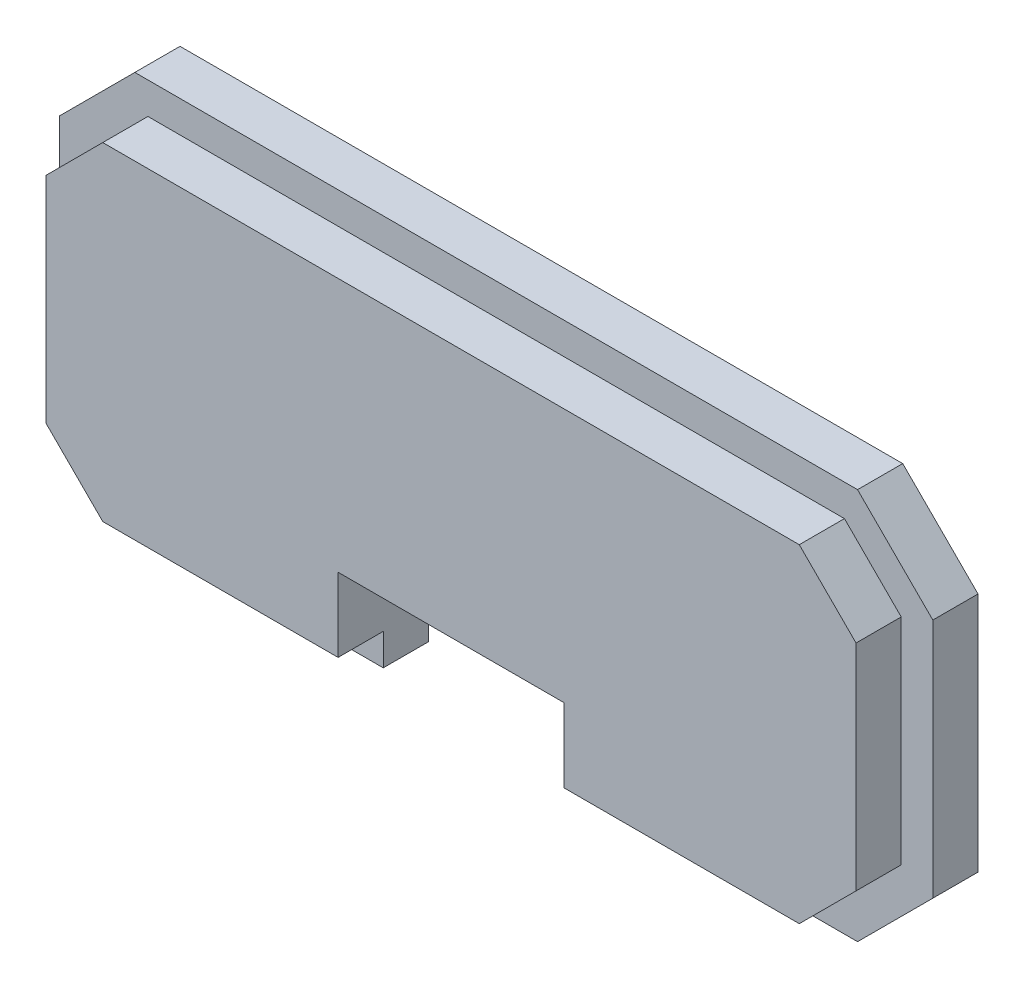
SolidWorks part; units mm, degrees
ref_plane "Front Plane" through (0, 0, 0) normal (0, 0, 1) x (1, 0, 0)
ref_plane "Top Plane" through (0, 0, 0) normal (0, 1, 0) x (1, 0, 0)
ref_plane "Right Plane" through (0, 0, 0) normal (1, 0, 0) x (0, 0, -1)
sketch "Sketch1" plane through (0, 0, 0) normal (0, 0, 1) x (1, 0, 0)
  line L0 (-232.0204, 85.6097) -> (-232.0204, 101.6097)
  line L1 (-232.0204, 85.6097) -> (-227.0204, 80.6097)
  line L2 (-179.0204, 80.6097) -> (-227.0204, 80.6097)
  line L3 (-179.0204, 80.6097) -> (-174.0204, 85.6097)
  line L4 (-174.0204, 101.6097) -> (-174.0204, 85.6097)
  line L5 (-174.0204, 101.6097) -> (-179.0204, 106.6097)
  line L6 (-227.0204, 106.6097) -> (-179.0204, 106.6097)
  line L7 (-227.0204, 106.6097) -> (-232.0204, 101.6097)
  line L8 (-232.0204, 93.6097) -> (-174.0204, 93.6097) construction
  line L9 (-203.0204, 106.6097) -> (-203.0204, 80.6097) construction
extrude "panel" add sketch "Sketch1" along normal blind 3
sketch "Sketch2" plane through (0, 0, 3) normal (0, 0, -1) x (-1, 0, 0)
  line L0 (174.0204, 85.6097) -> (174.0204, 101.6097) construction
  line L1 (179.0204, 80.6097) -> (174.0204, 85.6097) construction
  line L2 (227.0204, 80.6097) -> (179.0204, 80.6097) construction
  line L3 (232.0204, 85.6097) -> (227.0204, 80.6097) construction
  line L4 (232.0204, 101.6097) -> (232.0204, 85.6097) construction
  line L5 (227.0204, 106.6097) -> (232.0204, 101.6097) construction
  line L6 (179.0204, 106.6097) -> (227.0204, 106.6097) construction
  line L7 (174.0204, 101.6097) -> (179.0204, 106.6097) construction
  line L8 (174.0204, 85.6097) -> (174.0204, 101.6097) construction
  line L9 (179.0204, 80.6097) -> (174.0204, 85.6097) construction
  line L10 (227.0204, 80.6097) -> (179.0204, 80.6097) construction
  line L11 (232.0204, 85.6097) -> (227.0204, 80.6097) construction
  line L12 (232.0204, 101.6097) -> (232.0204, 85.6097) construction
  line L13 (227.0204, 106.6097) -> (232.0204, 101.6097) construction
  line L14 (179.0204, 106.6097) -> (227.0204, 106.6097) construction
  line L15 (174.0204, 101.6097) -> (179.0204, 106.6097) construction
  line L16 (176.1204, 86.4795) -> (176.1204, 100.7398)
  line L17 (176.1204, 100.7398) -> (179.8903, 104.5097)
  line L18 (179.8903, 104.5097) -> (226.1506, 104.5097)
  line L19 (226.1506, 104.5097) -> (229.9204, 100.7398)
  line L20 (229.9204, 100.7398) -> (229.9204, 86.4795)
  line L21 (229.9204, 86.4795) -> (226.1506, 82.7097)
  line L22 (226.1506, 82.7097) -> (179.8903, 82.7097)
  line L23 (179.8903, 82.7097) -> (176.1204, 86.4795)
  dimension "D1" = 2.1
extrude "insert" add sketch "Sketch2" against normal blind 3 contours L16 L17 L18 L19 L20 L21 L22 L23
sketch "Sketch3" plane through (0, 0, 0) normal (0, 0, 1) x (1, 0, 0)
  line L0 (-227.0204, 80.6097) -> (-179.0204, 80.6097) construction
  line L1 (-210.5204, 80.6097) -> (-195.5204, 80.6097)
  line L2 (-210.5204, 80.6097) -> (-210.5204, 87.6097)
  line L3 (-210.5204, 87.6097) -> (-195.5204, 87.6097)
  line L4 (-195.5204, 80.6097) -> (-195.5204, 87.6097)
  point P6 (-203.0204, 80.6097)
  point P7 (-203.0204, 80.6097)
  dimension "D1" = 15
  dimension "D2" = 7
extrude "Cut-Extrude1" cut sketch "Sketch3" along normal through all
